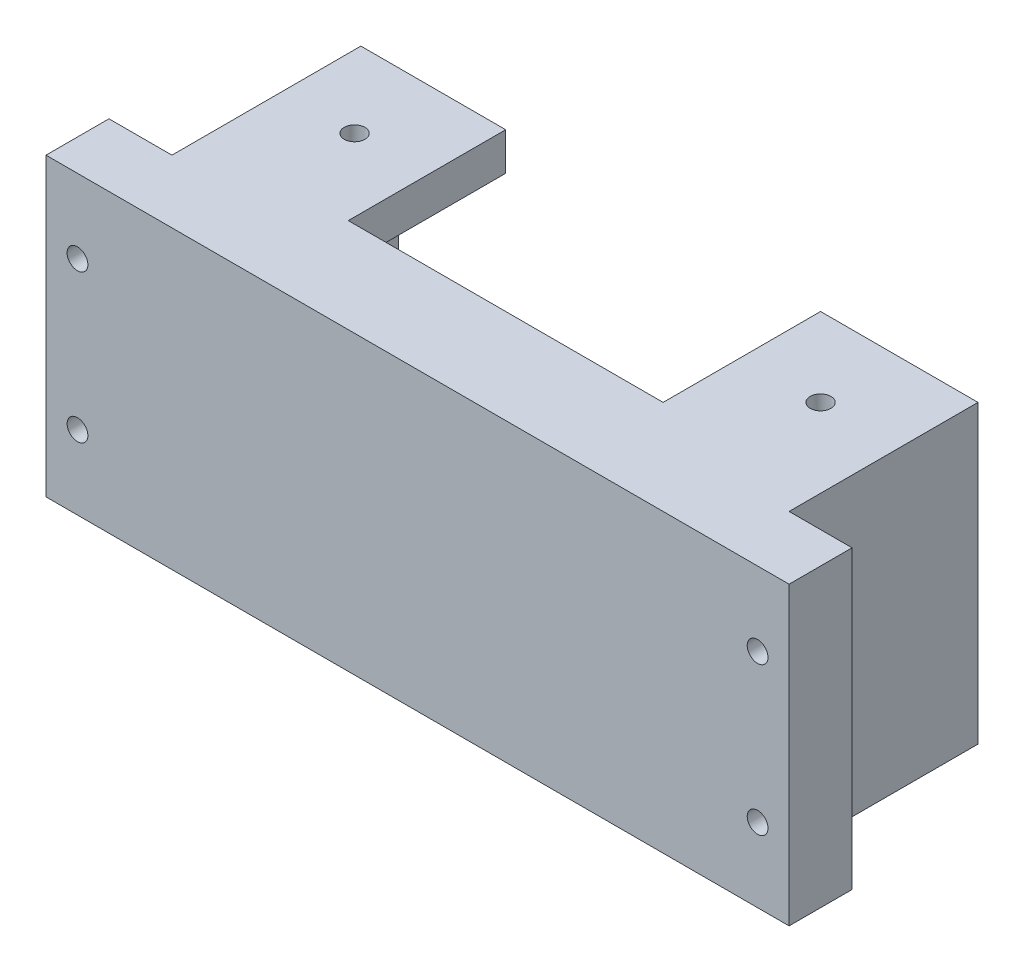
SolidWorks part; units mm, degrees
ref_plane "Front Plane" through (0, 0, 0) normal (0, 0, 1) x (1, 0, 0)
ref_plane "Top Plane" through (0, 0, 0) normal (0, 1, 0) x (1, 0, 0)
ref_plane "Right Plane" through (0, 0, 0) normal (1, 0, 0) x (0, 0, -1)
sketch "Sketch2" plane through (0, 0, 0) normal (0, 1, 0) x (1, 0, 0)
  line L5 (-6, 69) -> (-6, 0)
  line L8 (0, -6) -> (86, -6)
  line L11 (92, 0) -> (92, 69)
  line L14 (86, 75) -> (0, 75)
  line L16 (0, 75) -> (-6, 75)
  line L17 (-6, 75) -> (-6, 69)
  line L18 (-6, 0) -> (-6, -6)
  line L19 (-6, -6) -> (0, -6)
  line L20 (86, -6) -> (92, -6)
  line L21 (92, -6) -> (92, 0)
  line L22 (92, 69) -> (92, 75)
  line L23 (92, 75) -> (86, 75)
extrude "Boss-Extrude2" add sketch "Sketch2" along normal blind 75
sketch "Sketch3" plane through (0, 0, 0) normal (0, -1, 0) x (-1, 0, 0)
  line L0 (-92, -6) -> (-92, 4)
  line L1 (-92, -6) -> (-92, 75) construction
  line L2 (-92, 4) -> (-112, 4)
  line L3 (-112, 4) -> (-112, -6)
  line L4 (-112, -6) -> (-92, -6)
  line L5 (6, -6) -> (26, -6)
  line L6 (26, -6) -> (26, 4)
  line L7 (26, 4) -> (6, 4)
  line L8 (6, 75) -> (6, -6) construction
  line L9 (6, 4) -> (6, -6)
extrude "Boss-Extrude3" add sketch "Sketch3" against normal blind 75
sketch "Sketch4" plane through (0, 0, 0) normal (0, -1, 0) x (-1, 0, 0)
  line L0 (-92, 75) -> (-67, 75)
  line L2 (-92, 75) -> (6, 75) construction
  line L3 (-67, 75) -> (-67, 50)
  line L4 (-67, 50) -> (-17, 50)
  line L5 (-17, 50) -> (-17, 75)
  line L6 (-17, 75) -> (-17, 50)
  line L7 (-67, 50) -> (-17, 50)
  line L8 (-17, 75) -> (-67, 75)
  line M1 (6, 75) -> (-92, 75)
extrude "Cut-Extrude1" cut sketch "Sketch4" against normal blind 75 contours L4 L5 L3 M1
sketch "Sketch5" plane through (0, 0, 0) normal (0, -1, 0) x (-1, 0, 0)
  line L0 (-67, 22) -> (-67, -6)
  line L1 (26, -6) -> (-112, -6) construction
  line L3 (-17, 22) -> (-17, -6)
  line L4 (-17, -6) -> (-17, 22)
  line L5 (-67, 22) -> (-17, 22)
  line M7 (-112, -6) -> (26, -6)
extrude "Cut-Extrude2" cut sketch "Sketch5" against normal blind 75 contours L5 L0 L3 M7
sketch "Sketch6" plane through (0, 0, -75) normal (0, 0, -1) x (-1, 0, 0)
  line L2 (-86, 0) -> (-92, 0)
  line L4 (-92, 0) -> (-86, 0)
  line L5 (-86, 20) -> (-86, 55)
  line L6 (-86, 55) -> (-86, 20)
  line L10 (0, 20) -> (0, 55)
  line L14 (0, 55) -> (0, 20)
  line L16 (0, 37.5) -> (0, 55)
  line L17 (0, 55) -> (-86, 55)
  line L18 (-86, 55) -> (0, 55)
  line L19 (0, 55) -> (0, 37.5)
  line L20 (0, 37.5) -> (0, 20)
  line L21 (0, 20) -> (-86, 20)
  line M3 (-67, 0) -> (-67, 75)
extrude "Cut-Extrude3" cut sketch "Sketch6" against normal blind 25 contours L21 L17 L5 M3 | L21 L10 L14 L17 M3
sketch "Sketch7" plane through (0, 0, 0) normal (0, -1, 0) x (-1, 0, 0)
  line L0 (-112, 4) -> (-112, -6)
  line L1 (-112, -6) -> (-67, -6)
  line L2 (-67, -6) -> (-67, 22)
  line L3 (-67, 22) -> (-17, 22)
  line L4 (-17, 22) -> (-17, -6)
  line L5 (-17, -6) -> (26, -6)
  line L6 (26, -6) -> (26, 4)
  line L7 (26, 4) -> (6, 4)
  line L8 (6, 4) -> (6, 75)
  line L9 (6, 75) -> (-17, 75)
  line L10 (-17, 75) -> (-17, 50)
  line L11 (-17, 50) -> (-67, 50)
  line L12 (-67, 50) -> (-67, 75)
  line L13 (-67, 75) -> (-92, 75)
  line L14 (-92, 75) -> (-92, 4)
  line L15 (-92, 4) -> (-112, 4)
extrude "Cut-Extrude4" cut sketch "Sketch7" against normal blind 14
sketch "Sketch8" plane through (0, 75, 0) normal (0, 1, 0) x (1, 0, 0)
  line L0 (-26, 4) -> (-6, 4)
  line L1 (-6, 4) -> (-6, 75)
  line L2 (-6, 75) -> (17, 75)
  line L3 (17, 75) -> (17, 50)
  line L4 (17, 50) -> (67, 50)
  line L5 (67, 50) -> (67, 75)
  line L6 (67, 75) -> (92, 75)
  line L7 (92, 75) -> (92, 4)
  line L8 (92, 4) -> (112, 4)
  line L9 (112, 4) -> (112, -6)
  line L10 (112, -6) -> (67, -6)
  line L11 (67, -6) -> (67, 22)
  line L12 (67, 22) -> (17, 22)
  line L13 (67, 22) -> (17, 22) construction
  line L14 (17, 22) -> (17, -6)
  line L15 (17, -6) -> (-26, -6)
  line L16 (-26, -6) -> (-26, 4)
extrude "Cut-Extrude5" cut sketch "Sketch8" against normal blind 14
sketch "Sketch24" plane through (0, 14, 0) normal (0, -1, 0) x (-1, 0, 0)
  line L5 (-67, 50) -> (-67, 60)
  line L7 (-67, 50) -> (-67, 75) construction
  line L9 (-67, 60) -> (-17, 60)
  line L10 (-17, 75) -> (-17, 50) construction
  line L11 (-17, 60) -> (-17, 50)
  line L12 (-17, 50) -> (-67, 50)
extrude "Boss-Extrude4" add sketch "Sketch24" against normal blind 6
sketch "Sketch25" plane through (0, 61, 0) normal (0, 1, 0) x (1, 0, 0)
  line L0 (17, 50) -> (17, 60)
  line L1 (17, 60) -> (67, 60)
  line L2 (67, 75) -> (67, 50) construction
  line L3 (67, 60) -> (67, 50)
  line L4 (67, 50) -> (17, 50)
extrude "Boss-Extrude5" add sketch "Sketch25" against normal blind 6
sketch "Sketch26" plane through (0, 61, 0) normal (0, 1, 0) x (1, 0, 0)
  line L0 (-6, 75) -> (17, 60)
  line L1 (17, 60) -> (17, 67.5)
  line L2 (17, 60) -> (17, 75) construction
  line L3 (17, 67.5) -> (-6, 67.5)
  line L4 (-6, 75) -> (-6, 4) construction
  line L5 (-6, 67.5) -> (17, 67.5)
  line L6 (17, 67.5) -> (92, 67.5)
  line L7 (92, 4) -> (92, 75) construction
  line L8 (92, 67.5) -> (67, 75)
  line L9 (67, 75) -> (79.5, 71.25)
  line L10 (79.5, 71.25) -> (79.5, 67.5)
  circle A0 centre (5.5, 67.5) radius 2.7435
  circle A1 centre (79.5, 67.5) radius 2.8292
sketch "Sketch31" plane through (0, 61, 0) normal (0, 1, 0) x (1, 0, 0)
  line L0 (-6, 75) -> (17, 60)
  line L1 (17, 60) -> (17, 45)
  line L2 (17, 45) -> (-6, 45)
  line L3 (-6, 75) -> (-6, 4) construction
  line L4 (-6, 45) -> (92, 45)
  line L5 (92, 4) -> (92, 75) construction
  line L7 (67, -6) -> (112, -6) construction
  line L8 (92, -6) -> (-6, -6)
  line L9 (-26, -6) -> (17, -6) construction
  line L12 (-26, -6) -> (-26, 45)
  line L13 (-26, 45) -> (-6, 45)
  line L14 (-26, -6) -> (-6, -6)
  line L15 (92, -6) -> (112, -6)
  line L16 (112, -6) -> (112, 45)
  line L17 (112, 45) -> (92, 45)
extrude "Cut-Extrude7" cut sketch "Sketch31" against normal through all contours L4 L17 L16 L15 L8 L14 L12 L13
sketch "Sketch33" plane through (0, 61, 0) normal (0, 1, 0) x (1, 0, 0)
  line L0 (-6, 45) -> (-16, 45)
  line L1 (-16, 45) -> (-16, 55)
  line L2 (-16, 55) -> (-6, 55)
  line L3 (-6, 75) -> (-6, 45) construction
  line L4 (92, 55) -> (92, 45)
  line L5 (92, 45) -> (92, 75) construction
  line L6 (92, 45) -> (102, 45)
  line L7 (102, 45) -> (102, 55)
  line L8 (102, 55) -> (92, 55)
  line M3 (-6, 75) -> (-6, 45)
  line M5 (92, 45) -> (92, 75)
extrude "Boss-Extrude6" add sketch "Sketch33" against normal through all contours L2 L1 L0 M3 | L7 L8 L6 M5
sketch "Sketch34" plane through (0, 0, -55) normal (0, 0, -1) x (-1, 0, 0)
  line L0 (11, 14) -> (11, 61)
  line L1 (16, 14) -> (6, 14) construction
  line L2 (16, 61) -> (6, 61) construction
  line L3 (11, 61) -> (11, 37.5)
  line L4 (11, 37.5) -> (11, 49.25)
  line L5 (11, 49.25) -> (11, 37.5)
  line L6 (11, 37.5) -> (11, 14)
  circle A0 centre (11, 25.75) radius 3.3147
  circle A1 centre (11, 49.25) radius 2.2552
hole_wizard "M4x0.7 Tapped Hole8" positions "Sketch35" profile "Sketch36" tap size "M4x0.7" standard "ANSI Metric" end condition through all
sketch "Sketch35" plane through (0, 0, -55) normal (0, 0, -1) x (-1, 0, 0)
  point P0 (11, 25.75)
sketch "Sketch36" plane through (-11, 25.75, -55) normal (1, 0, 0) x (0, 1, 0)
  line L0 (0, 0) -> (0, 10)
  line L1 (0, 10) -> (1.65, 10)
  line L2 (1.65, 10) -> (1.65, 0)
  line L5 (1.65, 0) -> (0, 0)
  line L11 (0, -6.35) -> (0, 107.95) construction
  dimension "Thru Tap Drill Dia." = 3.3
  dimension "Thru Tap Drill Depth" = 10
cosmetic thread "Hole Thread8" parameters "D2"=4
hole_wizard "M4x0.7 Tapped Hole9" positions "Sketch37" profile "Sketch38" tap size "M4x0.7" standard "ANSI Metric" end condition through all
sketch "Sketch37" plane through (0, 0, -55) normal (0, 0, -1) x (-1, 0, 0)
  point P0 (11, 49.25)
sketch "Sketch38" plane through (-11, 49.25, -55) normal (1, 0, 0) x (0, 1, 0)
  line L0 (0, 0) -> (0, 10)
  line L1 (0, 10) -> (1.65, 10)
  line L2 (1.65, 10) -> (1.65, 0)
  line L5 (1.65, 0) -> (0, 0)
  line L11 (0, -6.35) -> (0, 107.95) construction
  dimension "Thru Tap Drill Dia." = 3.3
  dimension "Thru Tap Drill Depth" = 10
cosmetic thread "Hole Thread9" parameters "D2"=4
sketch "Sketch39" plane through (0, 0, -55) normal (0, 0, -1) x (-1, 0, 0)
  line L0 (-97, 61) -> (-97, 14)
  line L1 (-102, 61) -> (-92, 61) construction
  line L2 (-102, 14) -> (-92, 14) construction
  line L3 (-97, 14) -> (-97, 37.5)
  line L4 (-97, 37.5) -> (-97, 61)
  circle A0 centre (-97, 25.75) radius 4.1442
  circle A1 centre (-97, 49.25) radius 4.6819
hole_wizard "M4x0.7 Tapped Hole10" positions "Sketch40" profile "Sketch41" tap size "M4x0.7" standard "ANSI Metric" end condition through all
sketch "Sketch40" plane through (0, 0, -55) normal (0, 0, -1) x (-1, 0, 0)
  point P0 (-97, 49.25)
sketch "Sketch41" plane through (97, 49.25, -55) normal (1, 0, 0) x (0, 1, 0)
  line L0 (0, 0) -> (0, 10)
  line L1 (0, 10) -> (1.65, 10)
  line L2 (1.65, 10) -> (1.65, 0)
  line L5 (1.65, 0) -> (0, 0)
  line L11 (0, -6.35) -> (0, 107.95) construction
  dimension "Thru Tap Drill Dia." = 3.3
  dimension "Thru Tap Drill Depth" = 10
cosmetic thread "Hole Thread10" parameters "D2"=4
hole_wizard "M4x0.7 Tapped Hole11" positions "Sketch42" profile "Sketch43" tap size "M4x0.7" standard "ANSI Metric" end condition through all
sketch "Sketch42" plane through (0, 0, -55) normal (0, 0, -1) x (-1, 0, 0)
  point P0 (-97, 25.75)
sketch "Sketch43" plane through (97, 25.75, -55) normal (1, 0, 0) x (0, 1, 0)
  line L0 (0, 0) -> (0, 10)
  line L1 (0, 10) -> (1.65, 10)
  line L2 (1.65, 10) -> (1.65, 0)
  line L5 (1.65, 0) -> (0, 0)
  line L11 (0, -6.35) -> (0, 107.95) construction
  dimension "Thru Tap Drill Dia." = 3.3
  dimension "Thru Tap Drill Depth" = 10
cosmetic thread "Hole Thread11" parameters "D2"=4
ref_plane "Plane4" through (0, 20, -75) normal (0, 0, -1) x (-1, 0, 0)
sketch "Sketch44" plane through (0, 20, -75) normal (0, 0, -1) x (-1, 0, 0)
  line L0 (-17, -6) -> (-17, 0)
  line L1 (-17, 0) -> (0, 0)
  line L2 (0, 0) -> (0, 35)
  line L3 (0, 35) -> (-17, 35)
  line L4 (-17, 35) -> (-17, 41)
  line L5 (-17, 41) -> (6, 41)
  line L6 (6, 41) -> (6, -6)
  line L7 (6, -6) -> (-17, -6)
extrude "Boss-Extrude7" add sketch "Sketch44" along normal blind 10
sketch "Sketch45" plane through (0, 0, -75) normal (0, 0, -1) x (-1, 0, 0)
  line L0 (-67, 61) -> (-67, 55)
  line L1 (-67, 55) -> (-86, 55)
  line L2 (-86, 55) -> (-86, 20)
  line L3 (-86, 20) -> (-67, 20)
  line L4 (-67, 20) -> (-67, 14)
  line L5 (-67, 14) -> (-92, 14)
  line L6 (-92, 14) -> (-92, 61)
  line L7 (-92, 61) -> (-67, 61)
extrude "Boss-Extrude8" add sketch "Sketch45" along normal blind 10
sketch "Sketch46" plane through (0, 61, 0) normal (0, 1, 0) x (1, 0, 0)
  line L0 (17, 60) -> (-6, 60)
  line L1 (-6, 85) -> (-6, 55) construction
  line L2 (-6, 60) -> (5.5, 60)
  line L3 (5.5, 60) -> (5.5, 85)
  line L4 (-6, 85) -> (17, 85) construction
  line L5 (5.5, 85) -> (5.5, 72.5)
  line L6 (5.5, 72.5) -> (92, 72.5)
  line L7 (92, 55) -> (92, 85) construction
  line L8 (92, 72.5) -> (67, 72.5)
  line L9 (67, 85) -> (67, 60) construction
  line L10 (67, 72.5) -> (79.5, 72.5)
  circle A0 centre (79.5, 72.5) radius 3.137
  circle A1 centre (5.5, 72.5) radius 2.5846
hole_wizard "M4x0.7 Tapped Hole12" positions "Sketch47" profile "Sketch48" tap size "M4x0.7" standard "ANSI Metric" end condition through all
sketch "Sketch47" plane through (0, 61, 0) normal (0, 1, 0) x (1, 0, 0)
  point P0 (5.5, 72.5)
sketch "Sketch48" plane through (5.5, 61, -72.5) normal (1, 0, 0) x (0, 0, 1)
  line L0 (0, 0) -> (0, 47)
  line L1 (0, 47) -> (1.65, 47)
  line L2 (1.65, 47) -> (1.65, 0)
  line L5 (1.65, 0) -> (0, 0)
  line L11 (0, -6.35) -> (0, 107.95) construction
  dimension "Thru Tap Drill Dia." = 3.3
  dimension "Thru Tap Drill Depth" = 47
cosmetic thread "Hole Thread12" parameters "D2"=4
hole_wizard "M4x0.7 Tapped Hole13" positions "Sketch49" profile "Sketch50" tap size "M4x0.7" standard "ANSI Metric" end condition through all
sketch "Sketch49" plane through (0, 61, 0) normal (0, 1, 0) x (1, 0, 0)
  point P0 (79.5, 72.5)
sketch "Sketch50" plane through (79.5, 61, -72.5) normal (1, 0, 0) x (0, 0, 1)
  line L0 (0, 0) -> (0, 47)
  line L1 (0, 47) -> (1.65, 47)
  line L2 (1.65, 47) -> (1.65, 0)
  line L5 (1.65, 0) -> (0, 0)
  line L11 (0, -6.35) -> (0, 107.95) construction
  dimension "Thru Tap Drill Dia." = 3.3
  dimension "Thru Tap Drill Depth" = 47
cosmetic thread "Hole Thread13" parameters "D2"=4
